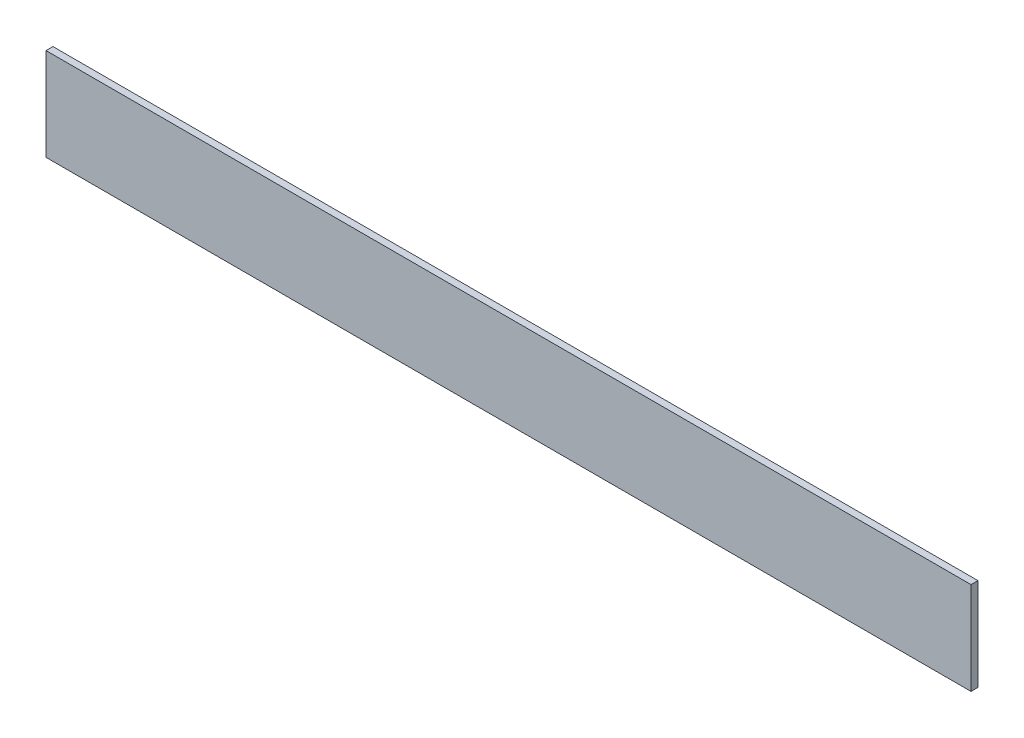
SolidWorks part; units mm, degrees
ref_plane "Front Plane" through (0, 0, 0) normal (0, 0, 1) x (1, 0, 0)
ref_plane "Top Plane" through (0, 0, 0) normal (0, 1, 0) x (1, 0, 0)
ref_plane "Right Plane" through (0, 0, 0) normal (1, 0, 0) x (0, 0, -1)
other "Configuration Table"
sketch "Sketch1" plane through (0, 0, 0) normal (0, 0, 1) x (1, 0, 0)
  line L1 (-48.7333, 76.6667) -> (967.2667, 76.6667)
  line L2 (-48.7333, 76.6667) -> (-48.7333, -24.9333)
  line L3 (-48.7333, -24.9333) -> (967.2667, -24.9333)
  line L4 (967.2667, 76.6667) -> (967.2667, -24.9333)
extrude "Extrude1" add sketch "Sketch1" along normal blind 7.62
